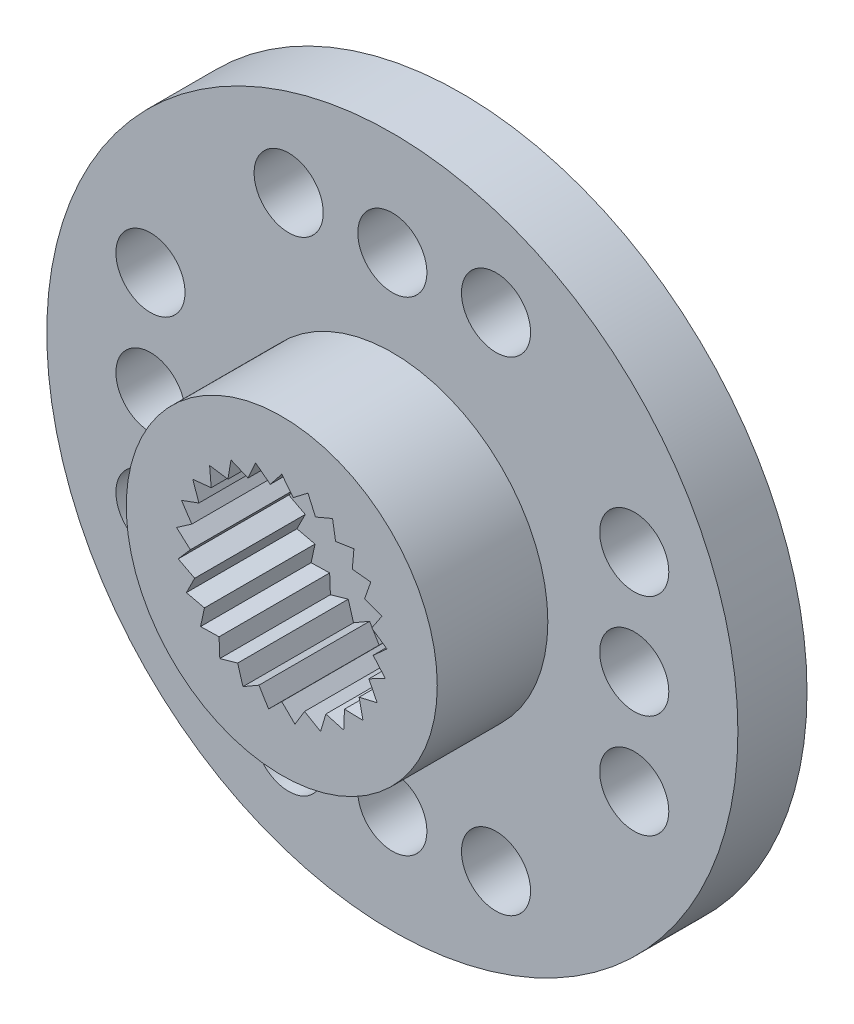
SolidWorks part; units mm, degrees
material "Du_servo"
ref_plane "Front Plane" through (0, 0, 0) normal (0, 0, 1) x (1, 0, 0)
ref_plane "Top Plane" through (0, 0, 0) normal (0, 1, 0) x (1, 0, 0)
ref_plane "Right Plane" through (0, 0, 0) normal (1, 0, 0) x (0, 0, -1)
sketch "Sketch1" plane through (0, 0, 0) normal (0, 0, 1) x (1, 0, 0)
  circle A0 centre (0, 0) radius 10
  circle A1 centre (0, 7) radius 1
  circle A2 centre (-3, 7) radius 1
  circle A3 centre (3, 7) radius 1
  circle A5 centre (7, 0) radius 1
  circle A6 centre (7, -3) radius 1
  circle A7 centre (7, 3) radius 1
  circle A8 centre (0, -7) radius 1
  circle A9 centre (-3, -7) radius 1
  circle A10 centre (3, -7) radius 1
  circle A11 centre (-7, 0) radius 1
  circle A12 centre (-7, 3) radius 1
  circle A13 centre (-7, -3) radius 1
  point P31 (0, 0)
  dimension "D1" = 20
  dimension "D2" = 2
  dimension "D3" = 2
  dimension "D4" = 2
  dimension "D5" = 4
extrude "Boss-Extrude1" add sketch "Sketch1" along normal blind 2
sketch "Sketch2" plane through (0, 0, 2) normal (0, 0, 1) x (1, 0, 0)
  line L0 (0.7585, 2.9542) -> (0.9755, 2.4639)
  line L1 (0.7585, 2.9542) -> (0.3321, 2.6291)
  line L2 (0, 3.05) -> (0.3321, 2.6291)
  line L3 (1.4693, 2.6727) -> (1.5576, 2.1439)
  line L4 (0, 3.05) -> (-0.3321, 2.6291)
  line L5 (1.4693, 2.6727) -> (0.9755, 2.4639)
  line L6 (2.0879, 2.2234) -> (2.0419, 1.6892)
  line L7 (2.0879, 2.2234) -> (1.5576, 2.1439)
  line L8 (2.5752, 1.6343) -> (2.3978, 1.1283)
  line L9 (2.5752, 1.6343) -> (2.0419, 1.6892)
  line L10 (2.9007, 0.9425) -> (2.6031, 0.4966)
  line L11 (2.9007, 0.9425) -> (2.3978, 1.1283)
  line L12 (3.044, 0.1915) -> (2.6448, -0.1664)
  line L13 (3.044, 0.1915) -> (2.6031, 0.4966)
  line L14 (2.996, -0.5715) -> (2.5203, -0.8189)
  line L15 (2.996, -0.5715) -> (2.6448, -0.1664)
  line L16 (2.7597, -1.2986) -> (2.2375, -1.4199)
  line L17 (2.7597, -1.2986) -> (2.5203, -0.8189)
  line L18 (2.3501, -1.9441) -> (1.814, -1.9318)
  line L19 (2.3501, -1.9441) -> (2.2375, -1.4199)
  line L20 (1.7927, -2.4675) -> (1.2766, -2.3222)
  line L21 (1.7927, -2.4675) -> (1.814, -1.9318)
  line L22 (1.1228, -2.8358) -> (0.659, -2.5667)
  line L23 (1.1228, -2.8358) -> (1.2766, -2.3222)
  line L24 (0.3823, -3.0259) -> (0, -2.65)
  line L25 (0.3823, -3.0259) -> (0.659, -2.5667)
  line L26 (-0.3823, -3.0259) -> (-0.659, -2.5667)
  line L27 (-0.3823, -3.0259) -> (0, -2.65)
  line L28 (-1.1228, -2.8358) -> (-1.2766, -2.3222)
  line L29 (-1.1228, -2.8358) -> (-0.659, -2.5667)
  line L30 (-1.7927, -2.4675) -> (-1.814, -1.9318)
  line L31 (-1.7927, -2.4675) -> (-1.2766, -2.3222)
  line L32 (-2.3501, -1.9441) -> (-2.2375, -1.4199)
  line L33 (-2.3501, -1.9441) -> (-1.814, -1.9318)
  line L34 (-2.7597, -1.2986) -> (-2.5203, -0.8189)
  line L35 (-2.7597, -1.2986) -> (-2.2375, -1.4199)
  line L36 (-2.996, -0.5715) -> (-2.6448, -0.1664)
  line L37 (-2.996, -0.5715) -> (-2.5203, -0.8189)
  line L38 (-3.044, 0.1915) -> (-2.6031, 0.4966)
  line L39 (-3.044, 0.1915) -> (-2.6448, -0.1664)
  line L40 (-2.9007, 0.9425) -> (-2.3978, 1.1283)
  line L41 (-2.9007, 0.9425) -> (-2.6031, 0.4966)
  line L42 (-2.5752, 1.6343) -> (-2.0419, 1.6892)
  line L43 (-2.5752, 1.6343) -> (-2.3978, 1.1283)
  line L44 (-2.0879, 2.2234) -> (-1.5576, 2.1439)
  line L45 (-2.0879, 2.2234) -> (-2.0419, 1.6892)
  line L46 (-1.4693, 2.6727) -> (-0.9755, 2.4639)
  line L47 (-1.4693, 2.6727) -> (-1.5576, 2.1439)
  line L48 (-0.7585, 2.9542) -> (-0.3321, 2.6291)
  line L49 (-0.7585, 2.9542) -> (-0.9755, 2.4639)
  circle A0 centre (0, 0) radius 4.5
  circle A1 centre (0, 0) radius 3.05 construction
  circle A2 centre (0, 0) radius 2.65 construction
  point P83 (0, 0)
  dimension "D1" = 9
  dimension "D2" = 6.1
  dimension "D3" = 5.3
  dimension "D4" = 25
extrude "Boss-Extrude2" add sketch "Sketch2" along normal blind 3.2
sketch "Sketch4" plane through (0, 0, 2) normal (0, 0, 1) x (1, 0, 0)
  circle A0 centre (0, 0) radius 1.5
  dimension "D1" = 3
extrude "Cut-Extrude1" cut sketch "Sketch4" against normal blind 2
